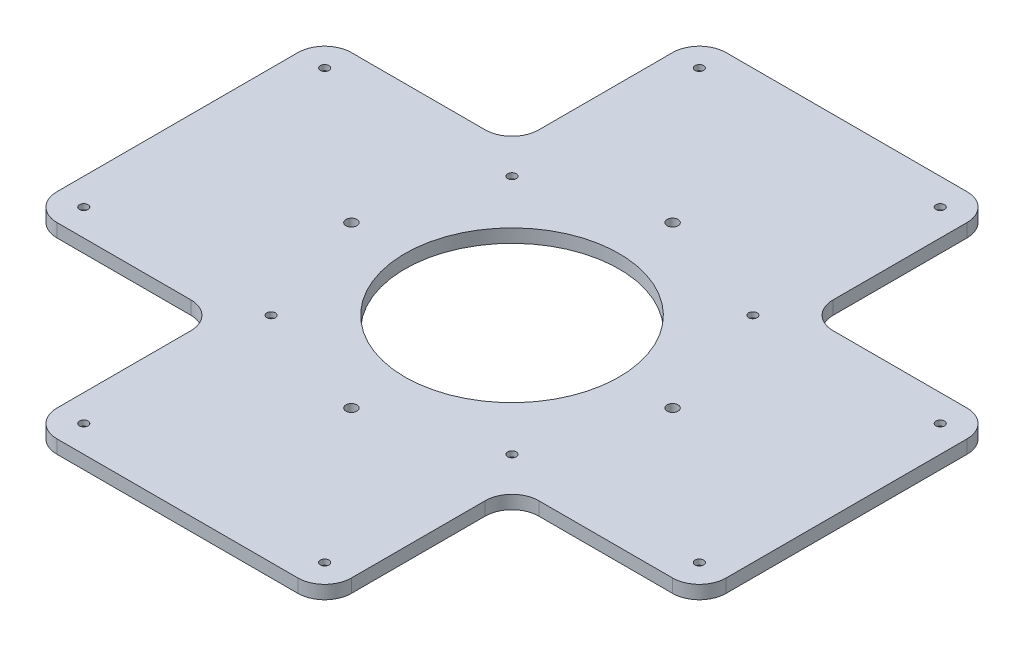
SolidWorks part; units mm, degrees
ref_plane "正面" through (0, 0, 0) normal (0, 0, 1) x (1, 0, 0)
ref_plane "平面" through (0, 0, 0) normal (0, 1, 0) x (1, 0, 0)
ref_plane "右側面" through (0, 0, 0) normal (1, 0, 0) x (0, 0, -1)
sketch "ｽｹｯﾁ1" plane through (0, 0, 0) normal (0, 1, 0) x (1, 0, 0)
  line L0 (0, 60) -> (0, 0) construction
  line L1 (-125, 125) -> (125, 125)
  line L2 (-125, 125) -> (-125, -125)
  line L3 (-125, -125) -> (125, -125)
  line L4 (125, 125) -> (125, -125)
  line L5 (-125, 125) -> (125, -125) construction
  line L6 (-125, -125) -> (125, 125) construction
  line L7 (0, 0) -> (-60, 0) construction
  line L8 (0, 0) -> (0, -60) construction
  circle A0 centre (0, 0) radius 40
  circle A1 centre (0, 60) radius 2.05
  circle A2 centre (60, 0) radius 2.05
  circle A3 centre (0, -60) radius 2.05
  circle A4 centre (-60, 0) radius 2.05
  point P0 (0, 0)
  dimension "D2" = 80
  dimension "D3" = 4.1
  dimension "D1" = 250
  dimension "D4" = 60
  dimension "D5" = 4
extrude "ﾎﾞｽ - 押し出し1" add sketch "ｽｹｯﾁ1" along normal blind 5
sketch "ｽｹｯﾁ2" plane through (0, 5, 0) normal (0, 1, 0) x (1, 0, 0)
  line L0 (0, 125) -> (0, -125) construction
  line L1 (-125, 125) -> (-55, 125)
  line L2 (-125, 125) -> (-125, 55)
  line L3 (-125, 55) -> (-55, 55)
  line L4 (-55, 125) -> (-55, 55)
  line L5 (125, 125) -> (-125, 125) construction
  line L6 (-125, -125) -> (125, -125) construction
  line L7 (125, 55) -> (55, 55)
  line L8 (125, -125) -> (125, 125) construction
  line L9 (125, 0) -> (-125, 0) construction
  line L10 (-125, 125) -> (-125, -125) construction
  line L11 (55, 125) -> (55, 55)
  line L12 (125, 125) -> (55, 125)
  line L13 (125, 125) -> (125, 55)
  line L14 (125, -125) -> (125, -55)
  line L15 (125, -125) -> (55, -125)
  line L16 (55, -125) -> (55, -55)
  line L17 (125, -55) -> (55, -55)
  line L18 (-125, -55) -> (-55, -55)
  line L19 (-55, -125) -> (-55, -55)
  line L20 (-125, -125) -> (-55, -125)
  line L21 (-125, -125) -> (-125, -55)
  line L22 (-45, 45) -> (-125, 125) construction
  line L23 (-45, 115) -> (-45, 45) construction
  line L24 (-45, 45) -> (-115, 45) construction
  line L25 (-125, 125) -> (-125, -125) construction
  line L26 (125, 125) -> (-125, 125) construction
  circle A0 centre (-45, 115) radius 1.6
  circle A1 centre (-45, 45) radius 1.6
  circle A2 centre (-115, 45) radius 1.6
  circle A3 centre (115, 45) radius 1.6
  circle A4 centre (45, 115) radius 1.6
  circle A5 centre (45, 45) radius 1.6
  circle A6 centre (-115, -45) radius 1.6
  circle A7 centre (-45, -45) radius 1.6
  circle A8 centre (-45, -115) radius 1.6
  circle A9 centre (45, -115) radius 1.6
  circle A10 centre (45, -45) radius 1.6
  circle A11 centre (115, -45) radius 1.6
  dimension "D3" = 3.2
  dimension "D1" = 70
  dimension "D2" = 70
  dimension "D4" = 10
  dimension "D5" = 10
  dimension "D6" = 70
  dimension "D7" = 70
extrude "ｶｯﾄ - 押し出し1" cut sketch "ｽｹｯﾁ2" against normal through all
fillet "ﾌｨﾚｯﾄ1" radius 10 12 edges at (125, 2.5, 55) (125, 2.5, -55) (55, 2.5, -125) (-55, 2.5, -125) (-125, 2.5, -55) (-125, 2.5, 55) (55, 2.5, 125) (-55, 2.5, 125) (55, 2.5, -55) (55, 2.5, 55) (-55, 2.5, 55) (-55, 2.5, -55)
sketch "ｽｹｯﾁ4" plane through (0, 0, 0) normal (0, -1, 0) x (1, 0, 0)
  line L0 (-125, 0) -> (0, 0) construction
  line L1 (-125, -45) -> (-125, 45) construction
  line L2 (0, 0) -> (0, 125) construction
  line L3 (-45, 125) -> (45, 125) construction
  circle A0 centre (-45, 115) radius 3
  circle A1 centre (-45, 45) radius 3
  circle A2 centre (-115, 45) radius 3
  circle A3 centre (115, 45) radius 3
  circle A4 centre (45, 45) radius 3
  circle A5 centre (45, 115) radius 3
  circle A6 centre (45, -115) radius 3
  circle A7 centre (45, -45) radius 3
  circle A8 centre (115, -45) radius 3
  circle A9 centre (-115, -45) radius 3
  circle A10 centre (-45, -45) radius 3
  circle A11 centre (-45, -115) radius 3
  dimension "D1" = 6
extrude "ｶｯﾄ - 押し出し3" cut sketch "ｽｹｯﾁ4" against normal blind 3
sketch "ｽｹｯﾁ5" plane through (0, 5, 0) normal (0, 1, 0) x (1, 0, 0)
  line L0 (45, -125) -> (125, -125) construction
  line L1 (125, -125) -> (125, -45) construction
